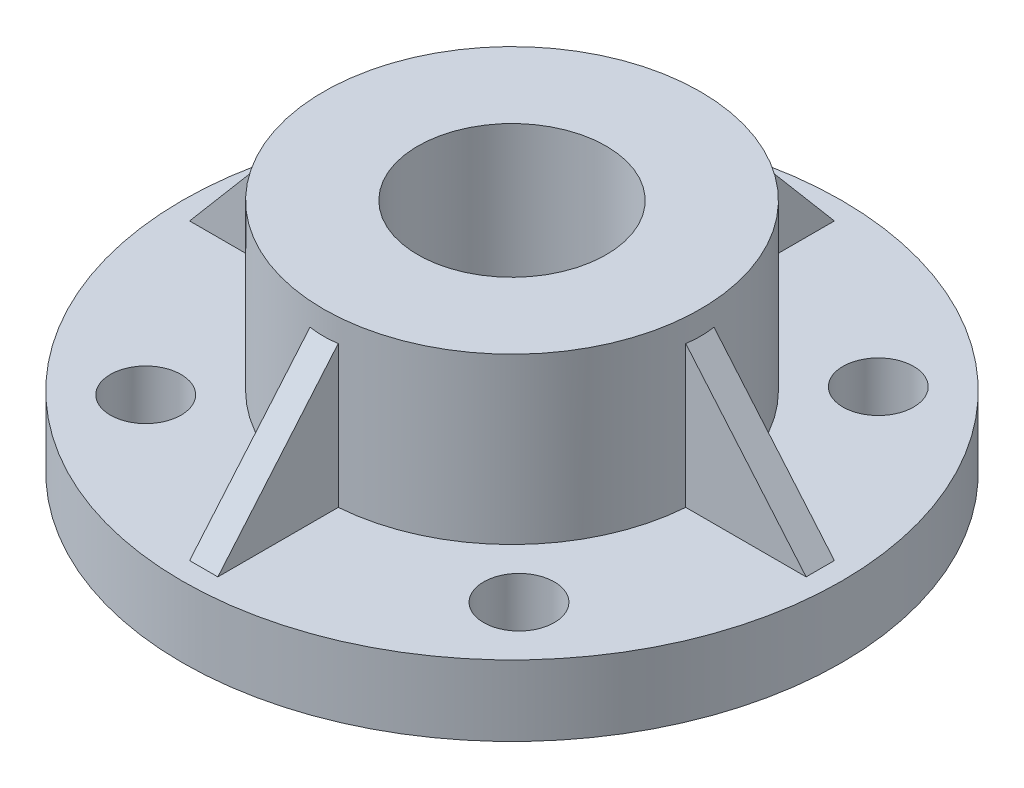
SolidWorks part; units mm, degrees
ref_plane "Front Plane" through (0, 0, 0) normal (0, 0, 1) x (1, 0, 0)
ref_plane "Top Plane" through (0, 0, 0) normal (0, 1, 0) x (1, 0, 0)
ref_plane "Right Plane" through (0, 0, 0) normal (1, 0, 0) x (0, 0, -1)
sketch "Sketch1" plane through (0, 0, 0) normal (0, 0, 1) x (1, 0, 0)
  line L0 (0, 0) -> (0, 199.1051) construction
  line L1 (20, 49.0898) -> (20, -0.9102)
  line L2 (20, -0.9102) -> (70, -0.9102)
  line L3 (20, 49.0898) -> (40, 49.0898)
  line L4 (40, 49.0898) -> (40, 14.0898)
  line L5 (40, 14.0898) -> (70, 14.0898)
  line L6 (70, 14.0898) -> (70, -0.9102)
  dimension "D1" = 50
  dimension "D2" = 15
  dimension "D3" = 20
  dimension "D4" = 50
  dimension "D5" = 20
revolve "Revolve1" add sketch "Sketch1" angle 360 about L0
sketch "Sketch2" plane through (0, 0, 0) normal (0, 0, 1) x (1, 0, 0)
  line L0 (-65, 14.6185) -> (-40, 44.0898)
  line L1 (-40, 49.0898) -> (-40, 14.0898) construction
  dimension "D1" = 5
  dimension "D2" = 5
rib "Rib1" sketch "Sketch2" sketch "Sketch2" thickness 6 extrusion direction parallel to sketch draft on no parameters "D1"=6
sketch "Sketch4" plane through (0, 0, 0) normal (0, 1, 0) x (1, 0, 0)
  line L0 (0, 71.6846) -> (0, -74.656) construction
  line L1 (-54.0565, 52.5708) -> (0, -1.4857) construction
  circle A0 centre (-39.6266, 38.1409) radius 7.5
  circle A1 centre (38.1409, 39.6266) radius 7.5
  circle A2 centre (39.6266, -38.1409) radius 7.5
  circle A3 centre (-38.1409, -39.6266) radius 7.5
  point P16 (0, 0)
  dimension "D2" = 15
  dimension "D4" = 4
  dimension "D1" = 45
  dimension "D3" = 55
extrude "Cut-Extrude2" cut sketch "Sketch4" along normal through all and the other way blind 10
pattern_circular "CirPattern6" count 4 over 360 about axis through (0, 0, 0) along (0, 1, 0) of "Rib1"
